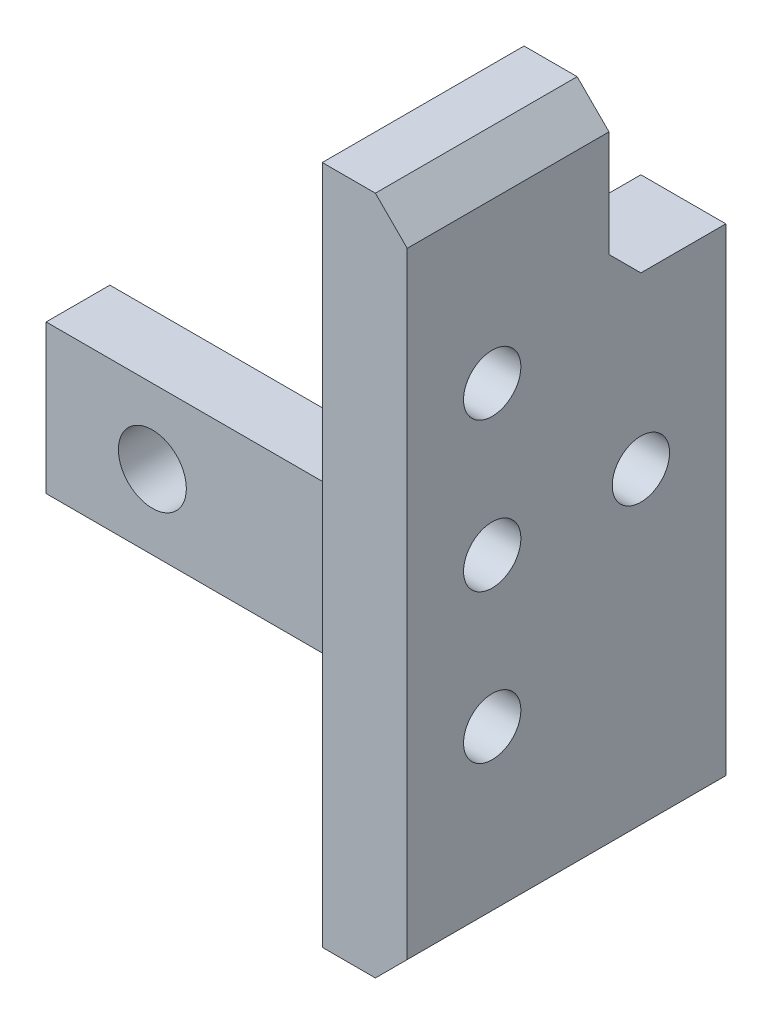
SolidWorks part; units mm, degrees
ref_plane "Płaszczyzna przednia" through (0, 0, 0) normal (0, 0, 1) x (1, 0, 0)
ref_plane "Płaszczyzna górna" through (0, 0, 0) normal (0, 1, 0) x (1, 0, 0)
ref_plane "Płaszczyzna prawa" through (0, 0, 0) normal (1, 0, 0) x (0, 0, -1)
sketch "Szkic1" plane through (0, 0, 0) normal (0, 0, 1) x (1, 0, 0)
  line L1 (0, -3.5) -> (25, -3.5)
  line L2 (0, -3.5) -> (0, 3.5)
  line L3 (0, 3.5) -> (25, 3.5)
  line L4 (25, -3.5) -> (25, 3.5)
  point P5 (0, 0)
  point P7 (0, 0)
  dimension "D1" = 25
  dimension "D2" = 7
extrude "Dodanie-wyciągnięcie1" add sketch "Szkic1" along normal blind 3 contours L2 L3 L4 L1
sketch "Szkic2" plane through (25, 0, 0) normal (1, 0, 0) x (0, 0, -1)
  line L1 (0, -3.5) -> (-15, -3.5)
  line L2 (0, -3.5) -> (0, 28.5)
  line L3 (0, 28.5) -> (-15, 28.5)
  line L4 (-15, -3.5) -> (-15, 28.5)
  dimension "D1" = 15
  dimension "D2" = 32
extrude "Dodanie-wyciągnięcie2" add sketch "Szkic2" along normal blind 4
sketch "Szkic3" plane through (0, 0, 3) normal (0, 0, 1) x (1, 0, 0)
  line L0 (0, -3.5) -> (0, 3.5) construction
  circle A0 centre (5, 0) radius 1.6
  circle A1 centre (20, 0) radius 1.6
  point P4 (0, 0)
  point P5 (0, 0)
  point P8 (0, 0)
  dimension "D1" = 3.2
  dimension "D2" = 15
  dimension "D3" = 5
extrude "Wytnij-wyciągnięcie1" cut sketch "Szkic3" against normal through all
sketch "Szkic4" plane through (29, 0, 0) normal (1, 0, 0) x (0, 0, -1)
  line L1 (0, 28.5) -> (-5.5, 28.5)
  line L2 (0, 28.5) -> (0, 20.5)
  line L3 (0, 20.5) -> (-5.5, 20.5)
  line L4 (-5.5, 28.5) -> (-5.5, 20.5)
  dimension "D1" = 5.5
  dimension "D2" = 8
extrude "Wytnij-wyciągnięcie2" cut sketch "Szkic4" against normal up to next
sketch "Szkic5" plane through (29, 0, 0) normal (1, 0, 0) x (0, 0, -1)
  line L0 (-15, 28.5) -> (-15, -3.5) construction
  line L1 (0, -3.5) -> (0, 20.5) construction
  circle A0 centre (-11, 12.5) radius 1.35
  circle A1 centre (-4, 12.5) radius 1.35
  circle A2 centre (-11, 5.5) radius 1.35
  circle A3 centre (-11, 19.5) radius 1.35
  point P8 (0, 0)
  point P11 (-15, 12.5)
  point P12 (0, 0)
  dimension "D3" = 2.7
  dimension "D1" = 4
  dimension "D2" = 4
  dimension "D4" = 7
  dimension "D5" = 7
extrude "Wytnij-wyciągnięcie3" cut sketch "Szkic5" against normal up to next
chamfer "Sfazowanie1" distance 1.5 angle 45 3 edges at (29, -3.5, 7.5) (29, 28.5, 10.25) (27, 20.5, 5.5)
chamfer "Sfazowanie2" distance 2 angle 45 1 edges at (25, 0, 3)
